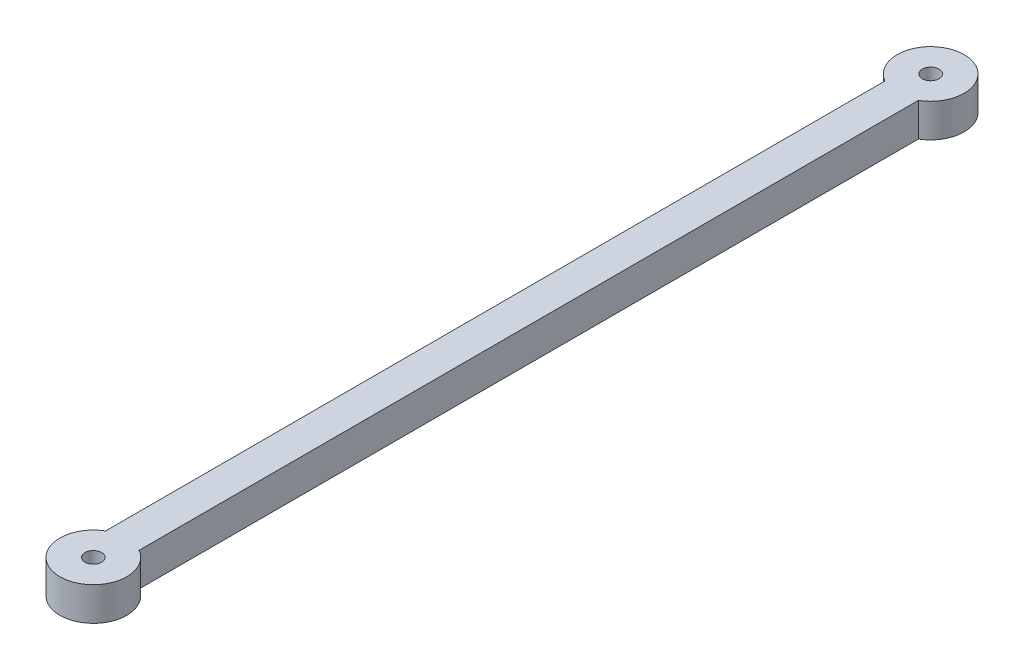
SolidWorks part; units mm, degrees
ref_plane "Front Plane" through (0, 0, 0) normal (0, 0, 1) x (1, 0, 0)
ref_plane "Top Plane" through (0, 0, 0) normal (0, 1, 0) x (1, 0, 0)
ref_plane "Right Plane" through (0, 0, 0) normal (1, 0, 0) x (0, 0, -1)
sketch "Sketch2" plane through (0, 0, 0) normal (0, 1, 0) x (1, 0, 0)
  line L0 (0, 0) -> (0, 150)
  line L2 (0, 0) -> (-3, 0)
  line L3 (0, 0) -> (0, 150)
  line L4 (0, 150) -> (-3, 150)
  line L5 (-3, 0) -> (-3, 150)
  line L6 (0, 150) -> (3, 150)
  line L7 (0, 150) -> (0, 0)
  line L8 (0, 0) -> (3, 0)
  line L9 (3, 150) -> (3, 0)
  circle A0 centre (0, 0) radius 6
  circle A1 centre (0, 0) radius 1.5
  circle A2 centre (0, 150) radius 6
  circle A3 centre (0, 150) radius 1.5
  dimension "D1" = 12
  dimension "D2" = 3
  dimension "D4" = 12
  dimension "D5" = 3
  dimension "D3" = 150
  dimension "D6" = 3
  dimension "D7" = 3
extrude "Boss-Extrude1" add sketch "Sketch2" along normal blind 6 contours A1 L2 L5 A0 L9 L8 | A1 L8 L9 A0 L7 | A1 L7 A0 L5 L2 | A2 L7 A0 L9 | A2 L5 A0 L7 | A3 L0 A2 L9 L6 | A3 L4 L5 A2 L0 | A3 L6 L9 A2 L5 L4
